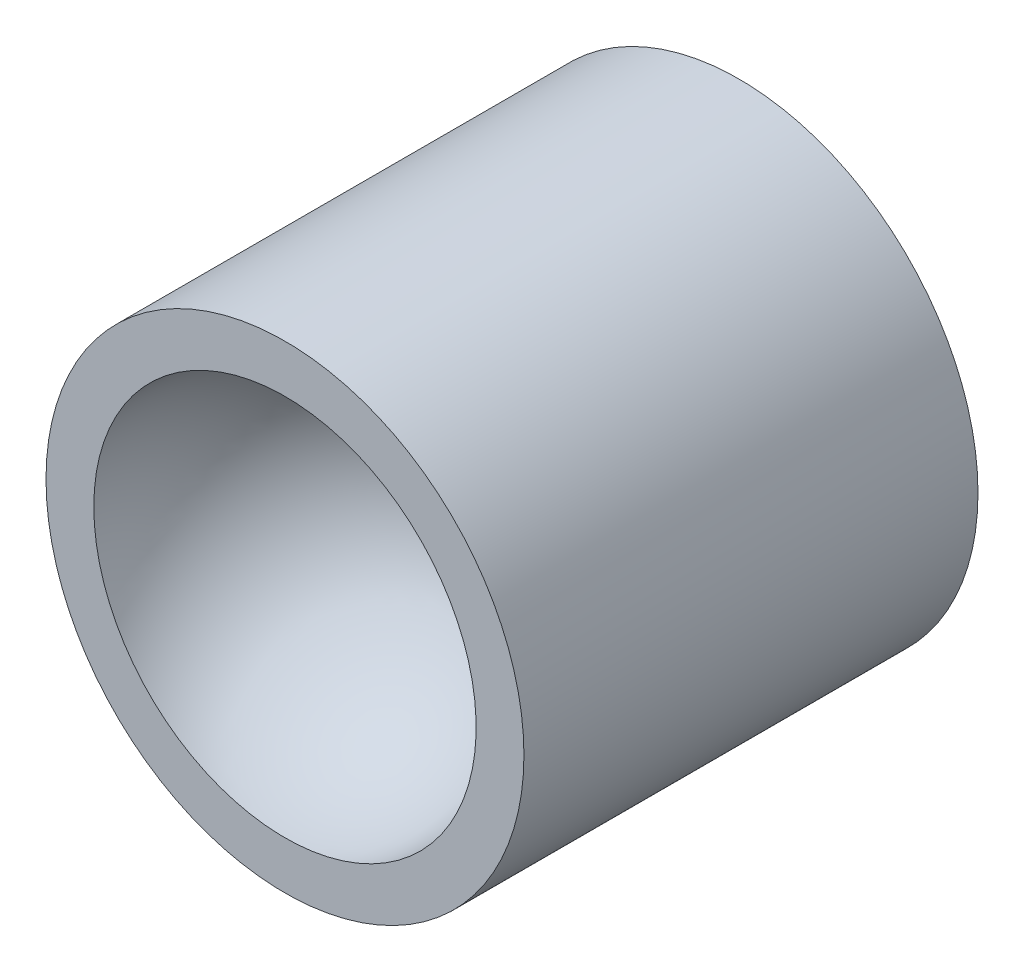
SolidWorks part; units mm, degrees
material "Acrylic (Medium-high impact)"
ref_plane "Front Plane" through (0, 0, 0) normal (0, 0, 1) x (1, 0, 0)
ref_plane "Top Plane" through (0, 0, 0) normal (0, 1, 0) x (1, 0, 0)
ref_plane "Right Plane" through (0, 0, 0) normal (1, 0, 0) x (0, 0, -1)
sketch "Sketch1" plane through (0, 0, 0) normal (0, 1, 0) x (1, 0, 0)
  line L0 (-8, 0) -> (-10, 0)
  line L1 (-10, 0) -> (-10, 19)
  line L2 (-10, 19) -> (0, 19)
  line L3 (0, 19) -> (0, 8)
  arc A0 (0, 8) -> (-8, 0) centre (0, 0) ccw
  dimension "D1" = 16
  dimension "D2" = 19
  dimension "D3" = 11
  dimension "D4" = 2
revolve "Revolve1" add sketch "Sketch1" angle 360 about L3
sketch "Sketch2" plane through (0, 0, -19) normal (0, 0, -1) x (-1, 0, 0)
  circle A0 centre (0, 0) radius 1.5
  dimension "D1" = 3
extrude "Cut-Extrude1" cut sketch "Sketch2" against normal blind 8
